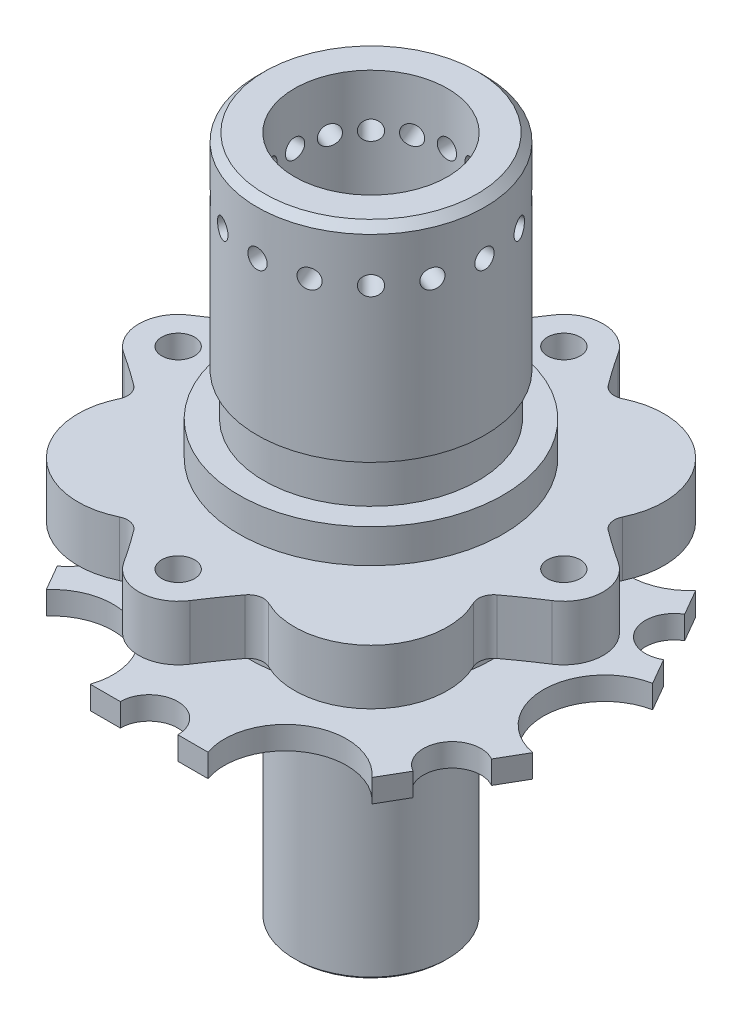
SolidWorks part; units mm, degrees
material "7075-T6 (SN)"
ref_plane "X-Y Datum" through (0, 0, 0) normal (0, 0, 1) x (1, 0, 0)
ref_plane "X-Z Datum" through (0, 0, 0) normal (0, 1, 0) x (1, 0, 0)
ref_plane "Y-Z Datum" through (0, 0, 0) normal (1, 0, 0) x (0, 0, -1)
sketch "Sketch1" plane through (0, 0, 0) normal (1, 0, 0) x (0, 0, -1)
  line L0 (0, 0) -> (-50000, 0) construction
  line L1 (0, 0) -> (0, 50000) construction
  line L2 (0, 0) -> (-25.0825, 0)
  line L3 (-25.0825, 0) -> (-25.0825, -12.319)
  line L5 (-25.0825, -17.0815) -> (-15.875, -17.0815)
  line L8 (0, -71.1505) -> (0, 0)
  line L9 (0, -71.1505) -> (-15.367, -71.1505)
  line L10 (-15.875, -17.0815) -> (-15.875, -70.6425)
  line L11 (-15.367, -71.1505) -> (-15.875, -70.6425)
  line L12 (-47.625, -12.319) -> (-47.625, -17.0815)
  line L13 (-47.625, -17.0815) -> (-25.0825, -17.0815)
  line L14 (-47.625, -12.319) -> (-25.0825, -12.319)
  dimension "D1" = 12.319
  dimension "D2" = 4.7625
  dimension "D3" = 54.069
  dimension "D4" = 47.625
  dimension "D5" = 45
  dimension "D6" = 90
  dimension "D7" = 31.75
  dimension "D8" = 0.508
  dimension "D9" = 4.7625
  dimension "D10" = 9.2075
sketch "Sketch2" plane through (0, 0, 0) normal (1, 0, 0) x (0, 0, -1)
  line L0 (0, 0) -> (-52.5, 0)
  line L1 (200000, 0) -> (-250000, 0) construction
  line L2 (-52.5, 0) -> (-52.5, 11.43)
  line L3 (-52.5, 11.43) -> (-27.4096, 11.43)
  line L4 (-27.4096, 11.43) -> (-27.4096, 18.43)
  line L5 (-27.4096, 18.43) -> (-22.225, 18.43)
  line L6 (-22.225, 18.43) -> (-22.225, 27.305)
  line L7 (-22.225, 27.305) -> (-23.6195, 27.305)
  line L10 (0, -200000) -> (0, 250000) construction
  line L11 (0, 69.85) -> (0, 0)
  line L15 (0, 69.85) -> (-22.032, 69.85)
  line L16 (-22.032, 69.85) -> (-23.6195, 68.2625)
  line L17 (-23.6195, 68.2625) -> (-23.6195, 27.305)
  line L18 (0, 0) -> (-50000, 0) construction
  line L19 (0, 0) -> (0, 50000) construction
  line L20 (0, 0) -> (0, -31242.0183) construction
  dimension "D1" = 11.43
  dimension "D2" = 58.42
  dimension "D3" = 47.2389
  dimension "D4" = 1.5875
  dimension "D5" = 45
  dimension "D6" = 54.8192
  dimension "D7" = 105
  dimension "D8" = 7
  dimension "D9" = 40.9575
  dimension "D10" = 44.45
revolve "Bearing Shaft/Flange Support" add sketch "Sketch1" angle 360 about L1
revolve "Drive Pin Support" add sketch "Sketch2" angle 360 about L19
sketch "Sketch5" plane through (0, 0, 0) normal (1, 0, 0) x (0, 0, -1)
  line L0 (0, 69.85) -> (15.875, 69.85)
  line L1 (22.032, 69.85) -> (-22.032, 69.85) construction
  line L4 (15.875, -9.525) -> (0, -9.525)
  line L5 (0, -9.525) -> (0, 69.85)
  line L6 (0, 0) -> (-50000, 0) construction
  line L7 (15.875, -9.525) -> (15.875, 69.85)
  line L8 (0, 0) -> (0, -50000) construction
  dimension "D1" = 79.375
  dimension "D4" = 31.75
revolve "Center Mass Removal" cut sketch "Sketch5" angle 360 about L8
hole_wizard "Drive Pin Holes" positions "Sketch6" profile "Sketch7" tap size "M8x1.25" standard "ANSI Metric"
sketch "Sketch6" plane through (0, 0, 0) normal (0, -1, 0) x (-1, 0, 0)
  circle A0 centre (0, 0) radius 40 construction
  point P0 (0, -40)
  dimension "D1" = 80
sketch "Sketch7" plane through (0, 0, 40) normal (1, 0, 0) x (0, 0, -1)
  line L0 (0, 0) -> (0, 69.85)
  line L1 (0, 69.85) -> (3.4, 69.85)
  line L2 (3.4, 69.85) -> (3.4, 0)
  line L5 (3.4, 0) -> (0, 0)
  line L11 (0, -6.35) -> (0, 107.95) construction
  dimension "Thru Tap Drill Dia." = 6.8
  dimension "Thru Tap Drill Depth" = 69.85
cosmetic thread "Hole Thread1" parameters "D2"=8
pattern_circular "Drive Pin Holes Pattern" count 4 over 360 about axis through (0, 0, 0) along (0, 1, 0) of "Drive Pin Holes"
cosmetic thread "Hole Thread2" parameters "D2"=8
cosmetic thread "Hole Thread3" parameters "D2"=8
cosmetic thread "Hole Thread4" parameters "D2"=8
sketch "Sketch8" plane through (0, 0, 0) normal (0, -1, 0) x (1, 0, 0)
  line L0 (0, 0) -> (-64.0279, 64.0279) construction
  line L1 (0, 0) -> (0, 72.7145) construction
  arc A0 (6.8518, 44.4362) -> (-6.8518, 44.4362) centre (0, 40) ccw
  arc A1 (6.8518, 44.4362) -> (13.2749, 35.4052) centre (113.4583, 113.4583) ccw
  arc A2 (44.4362, -6.8518) -> (44.4362, 6.8518) centre (40, 0) ccw
  arc A3 (44.4362, -6.8518) -> (44.4362, 6.8518) centre (40, 0) ccw
  arc A5 (44.4362, -6.8518) -> (35.4052, -13.2749) centre (113.4583, -113.4583) ccw
  circle A7 centre (0, 40) radius 3.4 construction
  circle A8 centre (0, 0) radius 52.5 construction
  circle A9 centre (0, 0) radius 40 construction
  arc A10 (-6.8518, -44.4362) -> (6.8518, -44.4362) centre (0, -40) ccw
  arc A11 (-6.8518, -44.4362) -> (6.8518, -44.4362) centre (0, -40) ccw
  arc A13 (-44.4362, 6.8518) -> (-44.4362, -6.8518) centre (-40, 0) ccw
  arc A14 (-44.4362, 6.8518) -> (-44.4362, -6.8518) centre (-40, 0) ccw
  arc A15 (-44.4362, 6.8518) -> (-35.4052, 13.2749) centre (-113.4583, 113.4583) ccw
  arc A16 (6.8518, 44.4362) -> (-6.8518, 44.4362) centre (0, 40) ccw
  circle A17 centre (0, 0) radius 52.5
  arc A18 (-6.8518, -44.4362) -> (-13.2749, -35.4052) centre (-113.4583, -113.4583) ccw
  arc A19 (-169.6965, 0.4112) -> (0.4112, -169.6965) centre (-113.4583, -113.4583) ccw [skipped]
  arc A20 (-13.2749, 35.4052) -> (-35.4052, 13.2749) centre (-22.4506, 22.4506) ccw
  arc A21 (-13.2749, 35.4052) -> (-6.8518, 44.4362) centre (-113.4583, 113.4583) ccw
  arc A22 (35.4052, 13.2749) -> (13.2749, 35.4052) centre (22.4506, 22.4506) ccw
  arc A23 (13.2749, -35.4052) -> (35.4052, -13.2749) centre (22.4506, -22.4506) ccw
  arc A24 (-35.4052, -13.2749) -> (-13.2749, -35.4052) centre (-22.4506, -22.4506) ccw
  arc A25 (35.4052, 13.2749) -> (44.4362, 6.8518) centre (113.4583, 113.4583) ccw
  arc A26 (13.2749, -35.4052) -> (6.8518, -44.4362) centre (113.4583, -113.4583) ccw
  arc A27 (-35.4052, -13.2749) -> (-44.4362, -6.8518) centre (-113.4583, -113.4583) ccw
  point P49 (0, 0)
  circle M10 centre (0, 0) radius 52.5
  dimension "D1" = 4.7625
  dimension "D2" = 45
  dimension "D3" = 254
  dimension "D4" = 80
  dimension "D6" = 31.75
  dimension "D7" = 31.75
  dimension "D5" = 4
  dimension "D8" = 4
extrude "Flange Support Cut" cut sketch "Sketch8" against normal up to next contours A10 A18 A13 A15 A0 A1 A2 A5 M10
sketch "Sketch10" plane through (0, -17.0815, 0) normal (0, -1, 0) x (1, 0, 0)
  line L0 (0, 0) -> (0, 50000) construction
  line L7 (0, 0) -> (50000, 0) construction
  line L8 (-5.969, -46.0335) -> (-12.2091, -46.0335)
  line L9 (5.969, -46.0375) -> (12.1938, -46.0375)
  line L10 (-42.8506, -17.8474) -> (-45.9707, -12.4434)
  line L11 (-36.8851, -28.1881) -> (-33.7727, -33.5789)
  line L12 (-36.8816, 28.186) -> (-33.7616, 33.5901)
  line L13 (-42.8541, 17.8494) -> (-45.9666, 12.4586)
  line L14 (5.969, 46.0335) -> (12.2091, 46.0335)
  line L15 (-5.969, 46.0375) -> (-12.1938, 46.0375)
  line L16 (42.8506, 17.8474) -> (45.9707, 12.4434)
  line L17 (36.8851, 28.1881) -> (33.7727, 33.5789)
  line L18 (36.8816, -28.186) -> (33.7616, -33.5901)
  line L19 (42.8541, -17.8494) -> (45.9666, -12.4586)
  arc A0 (-5.969, -46.0335) -> (5.969, -46.0375) centre (0, -46.0375) cw
  arc A1 (-42.8506, -17.8474) -> (-36.8851, -28.1881) centre (-39.8696, -23.0187) cw
  arc A3 (-36.8816, 28.186) -> (-42.8541, 17.8494) centre (-39.8696, 23.0188) cw
  circle A4 centre (0, 0) radius 47.625 construction
  arc A5 (5.969, 46.0335) -> (-5.969, 46.0375) centre (0, 46.0375) cw
  arc A6 (42.8506, 17.8474) -> (36.8851, 28.1881) centre (39.8696, 23.0187) cw
  arc A7 (36.8816, -28.186) -> (42.8541, -17.8494) centre (39.8696, -23.0188) cw
  circle A8 centre (0, 0) radius 47.625
  arc A9 (-33.7727, -33.5789) -> (-12.2091, -46.0335) centre (-24.2426, -41.9733) cw
  arc A10 (-45.9666, 12.4586) -> (-45.9707, -12.4434) centre (-48.4712, 0.008) cw
  arc A11 (-12.1938, 46.0375) -> (-33.7616, 33.5901) centre (-24.2287, 41.9813) cw
  arc A12 (33.7727, 33.5789) -> (12.2091, 46.0335) centre (24.2426, 41.9733) cw
  arc A13 (45.9666, -12.4586) -> (45.9707, 12.4434) centre (48.4712, -0.008) cw
  arc A14 (12.1938, -46.0375) -> (33.7616, -33.5901) centre (24.2287, -41.9813) cw
  point P42 (0, 0)
  point P60 (0, 0)
  dimension "D2" = 5.969
  dimension "D1" = 46.0375
  dimension "D5" = 95.25
  dimension "D6" = 12.7
  dimension "D3" = 6.2401
  dimension "D8" = 46.0375
  dimension "D4" = 6
  dimension "D7" = 6
extrude "Brake Hat Hex" cut sketch "Sketch10" along direction (0, -1, 0) on the side against the normal up to surface (4.7625 mm away)
sketch "Sketch11" plane through (0, -71.1505, 0) normal (0, -1, 0) x (1, 0, 0)
  circle A25 centre (0, 0) radius 9.525 construction
  circle A26 centre (0, 9.525) radius 3.175
  dimension "D1" = 19.05
  dimension "D2" = 6.35
hole_wizard "5/16 Clearnce" positions "Sketch27" profile "Sketch13" hole size "5/16" standard "ANSI Inch" end condition through all
sketch "Sketch27" plane through (0, -71.1505, 0) normal (0, -1, 0) x (-1, 0, 0)
  point P0 (0, 0)
sketch "Sketch13" plane through (0, -71.1505, 0) normal (1, 0, 0) x (0, 0, -1)
  line L0 (0, 0) -> (0, 141.0005)
  line L1 (0, 141.0005) -> (4.1021, 141.0005)
  line L2 (4.1021, 141.0005) -> (4.1021, 0)
  line L5 (4.1021, 0) -> (0, 0)
  line L11 (0, -6.35) -> (0, 107.95) construction
  dimension "Thru Hole Dia." = 8.2042
  dimension "Thru Hole Depth" = 141.0005
fillet "Hub Fillet" [suppressed] radius 0.7937
sketch "Sketch14" plane through (0, 0, 0) normal (1, 0, 0) x (0, 0, -1)
  line L0 (22.032, 69.85) -> (-22.032, 69.85) construction
  line L1 (0, 0) -> (-50000, 0) construction
  line L2 (0, 0) -> (0, -50000) construction
  circle A0 centre (0, 59.05) radius 2
  dimension "D2" = 4
  dimension "D1" = 10.8
extrude "Pin Holes" cut sketch "Sketch14" against normal through all
pattern_circular "Pin Hole Pattern" count 16 over 360 about axis through (0, 0, 0) along (0, -1, 0) of "Pin Holes"
chamfer "Floral Pattern Chamfer" [suppressed] distance 3.175 angle 45
sketch3d "3DSketch2"
  line L0 (0, 0, 0) -> (0, 0, -205.74)
  line L1 (0, 0, -205.74) -> (25.4, 0, -205.74)
  line L2 (0, 0, -205.74) -> (0, -25.4, -205.74)
  dimension "D1" = 25.4
  dimension "D2" = 25.4
  dimension "D3" = 205.74
extrude "Tripod Pins" cut sketch "Sketch11" against normal blind 12.7
thread "Main Big Threads" [suppressed] pitch 2.1167 start angle 0, offset 0.3048, length 0, pitch 2.1167, diameter 47.625
ref_plane "Plane1" through (-23.8125, 70.1548, 0) normal (0, 0, 1) x (-1, 0, 0)
sketch "Thread Profile1" plane through (-23.8125, 70.1548, 0) normal (0, 0, 1) x (-1, 0, 0)
  line L0 (0, 0) -> (0, 2.1167) construction
  line L11 (0, 0) -> (0, 1.8521)
  line L12 (0, 1.8521) -> (-1.1457, 1.1906)
  line L13 (-1.1457, 1.1906) -> (-1.1457, 0.6615)
  line L15 (-1.1457, 0.6615) -> (0, 0)
  line L17 (-1.1457, 0.926) -> (0, 0.926) construction
  point P2 (0, 0)
  dimension "Pitch" = 2.1167
  dimension "Profile_Angle" = 60
  dimension "Profile_Land" = 0.5292
  dimension "Profile_Height" = 1.1457
fillet "Fillet1" radius 3.175 8 edges at (-13.2749, 5.715, 35.4052) (-35.4052, 5.715, 13.2749) (-35.4052, 5.715, -13.2749) (-13.2749, 5.715, -35.4052) (13.2749, 5.715, -35.4052) (35.4052, 5.715, -13.2749) (35.4052, 5.715, 13.2749) (13.2749, 5.715, 35.4052)
pattern_circular "CirPattern1" count 4 over 360 about axis through (0, 0, 0) along (0, 1, 0) of "Tripod Pins"
sketch "Sketch28" plane through (0, -17.0815, 0) normal (0, -1, 0) x (1, 0, 0)
  line L0 (0, 0) -> (0, 46.0375) construction
